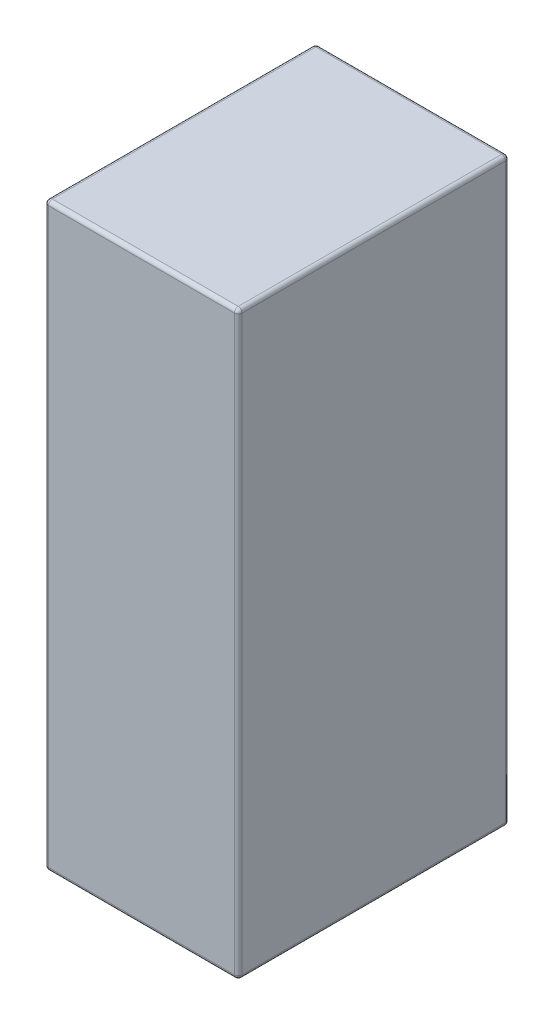
SolidWorks part; units mm, degrees
ref_plane "Front" through (0, 0, 0) normal (0, 0, 1) x (1, 0, 0)
ref_plane "Top" through (0, 0, 0) normal (0, 1, 0) x (1, 0, 0)
ref_plane "Right" through (0, 0, 0) normal (1, 0, 0) x (0, 0, -1)
sketch "Sketch1" plane through (0, 0, 0) normal (0, 1, 0) x (1, 0, 0)
  line L1 (-25, -35) -> (25, -35)
  line L2 (-25, -35) -> (-25, 35)
  line L3 (-25, 35) -> (25, 35)
  line L4 (25, -35) -> (25, 35)
  line L5 (-25, -35) -> (25, 35) construction
  line L6 (-25, 35) -> (25, -35) construction
  point P0 (0, 0)
  dimension "D1" = 50
  dimension "D2" = 70
extrude "Boss-Extrude1" add sketch "Sketch1" along normal mid plane 150
fillet "Fillet1" radius 1 12 edges at (25, 0, -35) (-25, 0, -35) (-25, 0, 35) (25, 0, 35) (0, -75, -35) (-25, -75, 0) (0, -75, 35) (25, -75, 0) (0, 75, 35) (-25, 75, 0) (0, 75, -35) (25, 75, 0)
